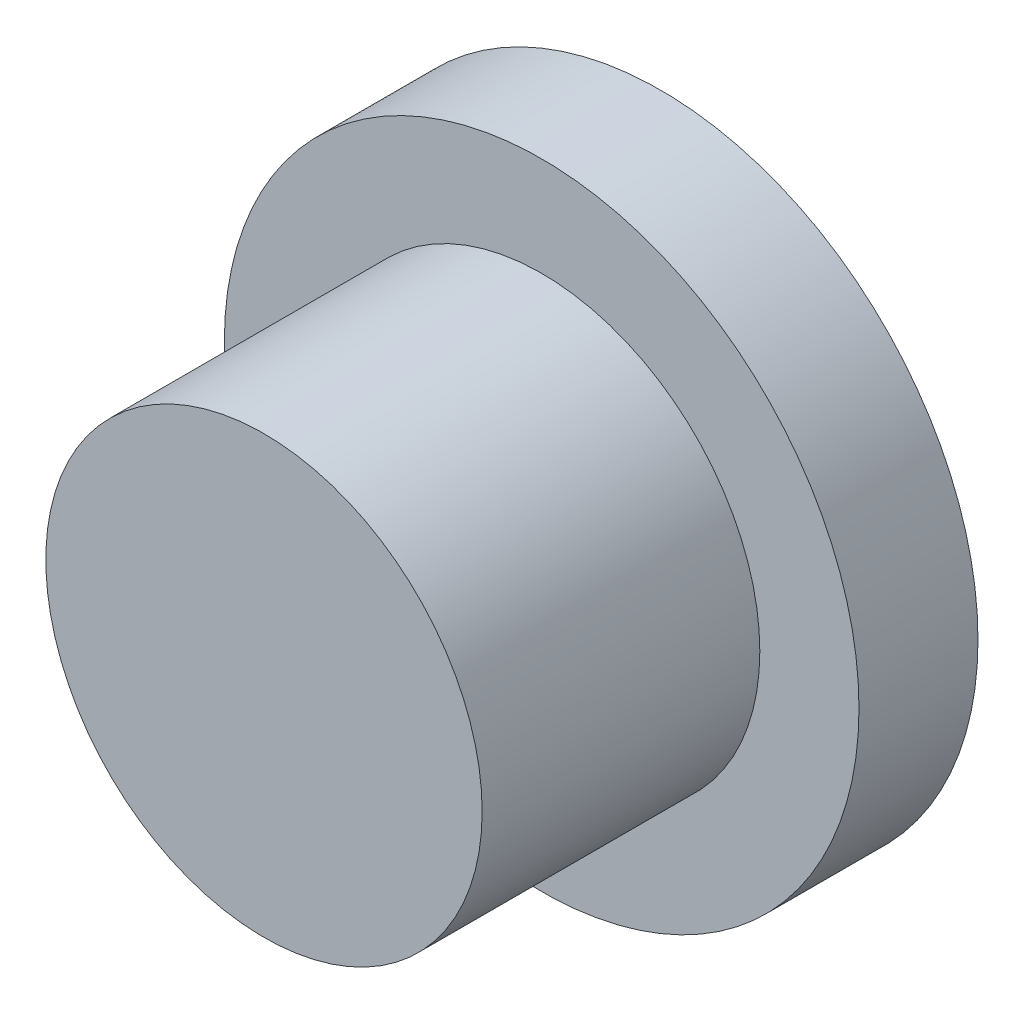
SolidWorks part; units mm, degrees
ref_plane "Front Plane" through (0, 0, 0) normal (0, 0, 1) x (1, 0, 0)
ref_plane "Top Plane" through (0, 0, 0) normal (0, 1, 0) x (1, 0, 0)
ref_plane "Right Plane" through (0, 0, 0) normal (1, 0, 0) x (0, 0, -1)
sketch "Plug Shaft Sketch" plane through (0, 0, 0) normal (0, 0, 1) x (1, 0, 0)
  circle A0 centre (0, 0) radius 11
  dimension "D1" = 22
extrude "Plug Shaft" add sketch "Plug Shaft Sketch" along normal blind 20
sketch "Plug Head Sketch" plane through (0, 0, 0) normal (0, 0, 1) x (1, 0, 0)
  circle A0 centre (0, 0) radius 16
  dimension "D1" = 32
extrude "Plug Head" add sketch "Plug Head Sketch" along normal blind 6
